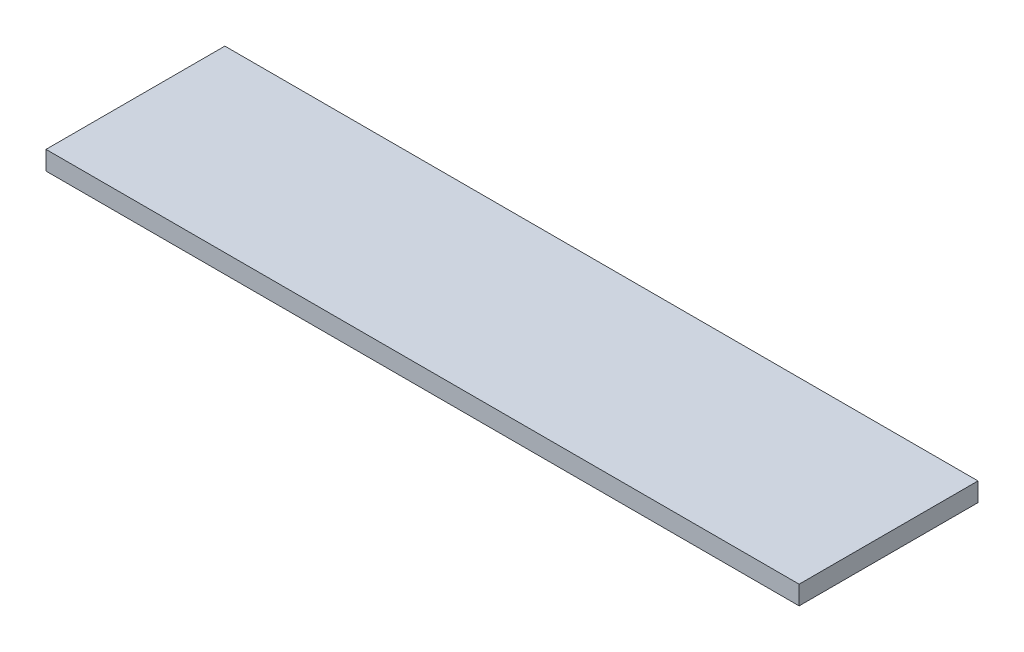
SolidWorks part; units mm, degrees
ref_plane "Front Plane" through (0, 0, 0) normal (0, 0, 1) x (1, 0, 0)
ref_plane "Top Plane" through (0, 0, 0) normal (0, 1, 0) x (1, 0, 0)
ref_plane "Right Plane" through (0, 0, 0) normal (1, 0, 0) x (0, 0, -1)
sketch "Sketch1" plane through (0, 0, 0) normal (0, 1, 0) x (1, 0, 0)
  line L1 (-200, 47.5) -> (200, 47.5)
  line L2 (-200, 47.5) -> (-200, -47.5)
  line L3 (-200, -47.5) -> (200, -47.5)
  line L4 (200, 47.5) -> (200, -47.5)
  line L5 (-200, 47.5) -> (200, -47.5) construction
  line L6 (-200, -47.5) -> (200, 47.5) construction
  point P0 (0, 0)
  dimension "D1" = 95
  dimension "D2" = 400
extrude "Boss-Extrude1" add sketch "Sketch1" along normal blind 10
